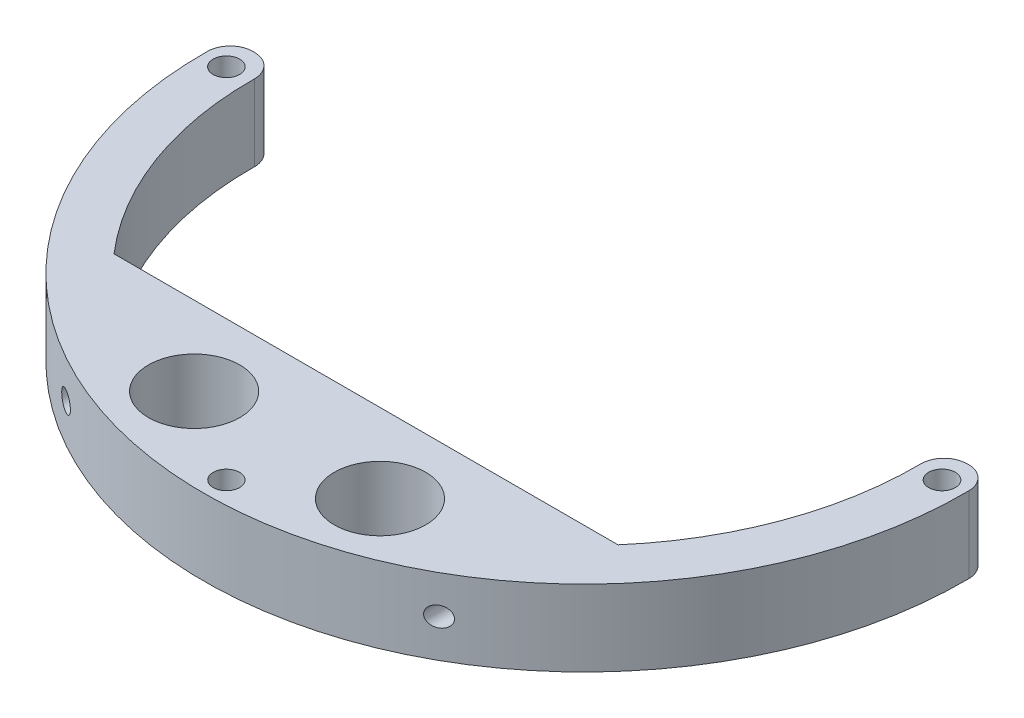
SolidWorks part; units mm, degrees
ref_plane "Front Plane" through (0, 0, 0) normal (0, 0, 1) x (1, 0, 0)
ref_plane "Top Plane" through (0, 0, 0) normal (0, 1, 0) x (1, 0, 0)
ref_plane "Right Plane" through (0, 0, 0) normal (1, 0, 0) x (0, 0, -1)
sketch "Sketch1" plane through (0, 0, 0) normal (0, 1, 0) x (1, 0, 0)
  line L0 (49.8593, 3.7482) -> (43.6644, 3.2233)
  line L2 (-49.8593, 3.7482) -> (-43.6644, 3.2233)
  line L4 (-33.0995, -28.6599) -> (33.0995, -28.6599)
  circle A2 centre (-47, 0) radius 1.75
  arc A4 (-33.0995, -28.6599) -> (-43.6644, 3.2233) centre (0, 0) cw
  circle A6 centre (-12.2081, -39.031) radius 6
  arc A9 (-49.8593, 3.7482) -> (49.8593, 3.7482) centre (0, 0) ccw
  circle A10 centre (0, -47) radius 1.7353
  circle A11 centre (12.2081, -39.031) radius 6
  arc A12 (33.0995, -28.6599) -> (43.6644, 3.2233) centre (0, 0) ccw
  circle A13 centre (47, 0) radius 1.75
  point P12 (0, -28.6599)
extrude "Boss-Extrude1" add sketch "Sketch1" along normal blind 10
fillet "Fillet2" radius 3 4 edges at (49.8593, 5, -3.7482) (43.6644, 5, -3.2233) (-49.8593, 5, -3.7482) (-43.6644, 5, -3.2233)
sketch "Sketch2" plane through (0, 0, 28.6599) normal (0, 0, -1) x (-1, 0, 0)
  line L0 (0, 0) -> (0, 10)
  line L1 (-33.0995, 0) -> (33.0995, 0) construction
  line L2 (-33.0995, 10) -> (33.0995, 10) construction
  line L3 (24.5, 5) -> (-24.5, 5)
  circle A0 centre (24.5, 5.0253) radius 1.3
  circle A1 centre (-24.5, 5) radius 1.3
  point P10 (-24.5, 5.0263)
  point P13 (0, 5)
  dimension "D1" = 49
extrude "Cut-Extrude1" cut sketch "Sketch2" against normal blind 20
